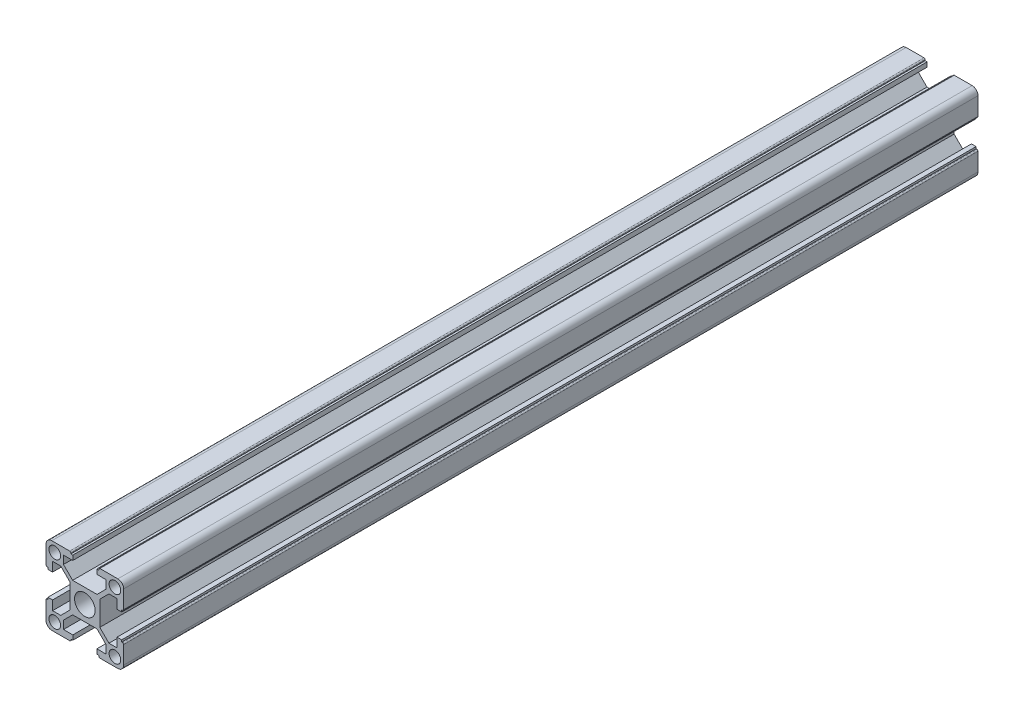
SolidWorks part; units mm, degrees
ref_plane "前视基准面" through (0, 0, 0) normal (0, 0, 1) x (1, 0, 0)
ref_plane "上视基准面" through (0, 0, 0) normal (0, 1, 0) x (1, 0, 0)
ref_plane "右视基准面" through (0, 0, 0) normal (1, 0, 0) x (0, 0, -1)
sketch "草图1" plane through (0, 0, 0) normal (0, 0, 1) x (1, 0, 0)
  line L0 (-7.75, 0) -> (0, 0) construction
  line L1 (7.75, -7.75) -> (-7.75, -7.75) construction
  line L2 (7.75, -7.75) -> (7.75, 7.75) construction
  line L3 (7.75, 7.75) -> (-7.75, 7.75) construction
  line L4 (-7.75, -7.75) -> (-7.75, 7.75) construction
  line L5 (7.75, -7.75) -> (-7.75, 7.75) construction
  line L6 (7.75, 7.75) -> (-7.75, -7.75) construction
  line L7 (0, 0) -> (0, 7.75) construction
  line L8 (3.1429, 3.85) -> (-3.1429, 3.85)
  line L9 (-3.1429, 3.85) -> (-5.5, 6.2071)
  line L10 (-5.5, 6.2071) -> (-5.5, 8.3)
  line L11 (-5.5, 8.3) -> (-3.1, 8.3)
  line L12 (-3.1, 8.3) -> (-3.1, 9.5)
  line L13 (-3.1, 9.5) -> (-3.6, 9.5)
  line L14 (-3.6, 9.5) -> (-3.6, 9.7)
  line L15 (-3.9, 10) -> (-8.5, 10)
  line L16 (-3.85, -3.1429) -> (-3.85, 3.1429)
  line L17 (-3.85, 3.1429) -> (-6.2071, 5.5)
  line L18 (-6.2071, 5.5) -> (-8.3, 5.5)
  line L19 (-8.3, 5.5) -> (-8.3, 3.1)
  line L20 (-9.5, 3.1) -> (-9.5, 3.6)
  line L21 (-8.3, 3.1) -> (-9.5, 3.1)
  line L22 (-9.5, 3.6) -> (-9.7, 3.6)
  line L23 (-10, 3.9) -> (-10, 8.5)
  line L24 (5.5, 8.3) -> (3.1, 8.3)
  line L25 (3.6, 9.5) -> (3.6, 9.7)
  line L26 (3.1, 9.5) -> (3.6, 9.5)
  line L27 (3.1, 8.3) -> (3.1, 9.5)
  line L28 (5.5, 6.2071) -> (5.5, 8.3)
  line L29 (3.1429, 3.85) -> (5.5, 6.2071)
  line L30 (3.85, -3.1429) -> (3.85, 3.1429)
  line L31 (3.85, 3.1429) -> (6.2071, 5.5)
  line L32 (9.5, 3.6) -> (9.7, 3.6)
  line L33 (8.3, 3.1) -> (9.5, 3.1)
  line L34 (9.5, 3.1) -> (9.5, 3.6)
  line L35 (8.3, 5.5) -> (8.3, 3.1)
  line L36 (6.2071, 5.5) -> (8.3, 5.5)
  line L37 (10, 3.9) -> (10, 8.5)
  line L38 (3.9, 10) -> (8.5, 10)
  line L39 (-9.5, -3.6) -> (-9.7, -3.6)
  line L40 (-8.3, -3.1) -> (-9.5, -3.1)
  line L41 (-9.5, -3.1) -> (-9.5, -3.6)
  line L42 (-8.3, -5.5) -> (-8.3, -3.1)
  line L43 (-6.2071, -5.5) -> (-8.3, -5.5)
  line L44 (-3.85, -3.1429) -> (-6.2071, -5.5)
  line L45 (-3.1429, -3.85) -> (-5.5, -6.2071)
  line L46 (-5.5, -6.2071) -> (-5.5, -8.3)
  line L47 (-3.6, -9.5) -> (-3.6, -9.7)
  line L48 (-3.1, -9.5) -> (-3.6, -9.5)
  line L49 (-3.1, -8.3) -> (-3.1, -9.5)
  line L50 (-5.5, -8.3) -> (-3.1, -8.3)
  line L51 (5.5, -6.2071) -> (5.5, -8.3)
  line L52 (3.1, -8.3) -> (3.1, -9.5)
  line L53 (3.1, -9.5) -> (3.6, -9.5)
  line L54 (3.6, -9.5) -> (3.6, -9.7)
  line L55 (5.5, -8.3) -> (3.1, -8.3)
  line L56 (3.1429, -3.85) -> (5.5, -6.2071)
  line L57 (3.1429, -3.85) -> (-3.1429, -3.85)
  line L58 (3.85, -3.1429) -> (6.2071, -5.5)
  line L59 (6.2071, -5.5) -> (8.3, -5.5)
  line L60 (8.3, -5.5) -> (8.3, -3.1)
  line L61 (9.5, -3.1) -> (9.5, -3.6)
  line L62 (8.3, -3.1) -> (9.5, -3.1)
  line L63 (9.5, -3.6) -> (9.7, -3.6)
  line L64 (3.9, -10) -> (8.5, -10)
  line L65 (10, -3.9) -> (10, -8.5)
  line L66 (-10, -3.9) -> (-10, -8.5)
  line L67 (-3.9, -10) -> (-8.5, -10)
  circle A0 centre (0, 0) radius 2.65
  circle A1 centre (-7.75, 7.75) radius 1.5
  circle A2 centre (7.75, 7.75) radius 1.5
  circle A3 centre (7.75, -7.75) radius 1.5
  circle A4 centre (-7.75, -7.75) radius 1.5
  arc A5 (-10, -8.5) -> (-8.5, -10) centre (-8.5, -8.5) ccw
  arc A6 (8.5, -10) -> (10, -8.5) centre (8.5, -8.5) ccw
  arc A7 (10, 8.5) -> (8.5, 10) centre (8.5, 8.5) ccw
  arc A8 (-8.5, 10) -> (-10, 8.5) centre (-8.5, 8.5) ccw
  arc A9 (3.6, -9.7) -> (3.9, -10) centre (3.9, -9.7) ccw
  arc A10 (-3.6, -9.7) -> (-3.9, -10) centre (-3.9, -9.7) cw
  arc A11 (-9.7, -3.6) -> (-10, -3.9) centre (-9.7, -3.9) ccw
  arc A12 (9.7, -3.6) -> (10, -3.9) centre (9.7, -3.9) cw
  arc A13 (9.7, 3.6) -> (10, 3.9) centre (9.7, 3.9) ccw
  arc A14 (-9.7, 3.6) -> (-10, 3.9) centre (-9.7, 3.9) cw
  arc A15 (3.6, 9.7) -> (3.9, 10) centre (3.9, 9.7) cw
  arc A16 (-3.6, 9.7) -> (-3.9, 10) centre (-3.9, 9.7) ccw
  point P46 (0, 3.85)
  point P56 (-3.85, 0)
  point P78 (3.85, 0)
  point P87 (-10, -10)
  point P90 (10, -10)
  point P93 (10, 10)
  point P96 (-10, 10)
  point P99 (3.6, -10)
  point P102 (-3.6, -10)
  point P105 (-10, -3.6)
  point P108 (10, -3.6)
  point P111 (10, 3.6)
  point P114 (-10, 3.6)
  point P117 (3.6, 10)
  point P120 (-3.6, 10)
  dimension "D1" = 5.3
  dimension "D2" = 3
  dimension "D11" = 1.5
  dimension "D12" = 2.25
  dimension "D13" = 0.3
  dimension "D3" = 7.7
  dimension "D4" = 6.2
  dimension "D5" = 1.7
  dimension "D6" = 1.2
  dimension "D7" = 20
  dimension "D8" = 7.2
  dimension "D9" = 11
  dimension "D10" = 1
extrude "凸台-拉伸1" add sketch "草图1" along normal mid plane 220
sketch "草图4" plane through (3.85, 0, 0) normal (1, 0, 0) x (0, 0, -1)
  line L0 (100, 0) -> (-100, 0) construction
  line L1 (-110, -3.1429) -> (-110, 3.1429) construction
  circle A0 centre (-100, 0) radius 2
  circle A1 centre (100, 0) radius 2
  circle A4 centre (-10, 0) radius 2
  circle A5 centre (10, 0) radius 2
  point P4 (0, 0)
  dimension "D1" = 4
  dimension "D2" = 10
  dimension "D5" = 10
  dimension "D6" = 10
extrude "切除-拉伸3" cut sketch "草图4" against normal through all
equation "\"D6@草图4\"=\"D5@草图4\""
